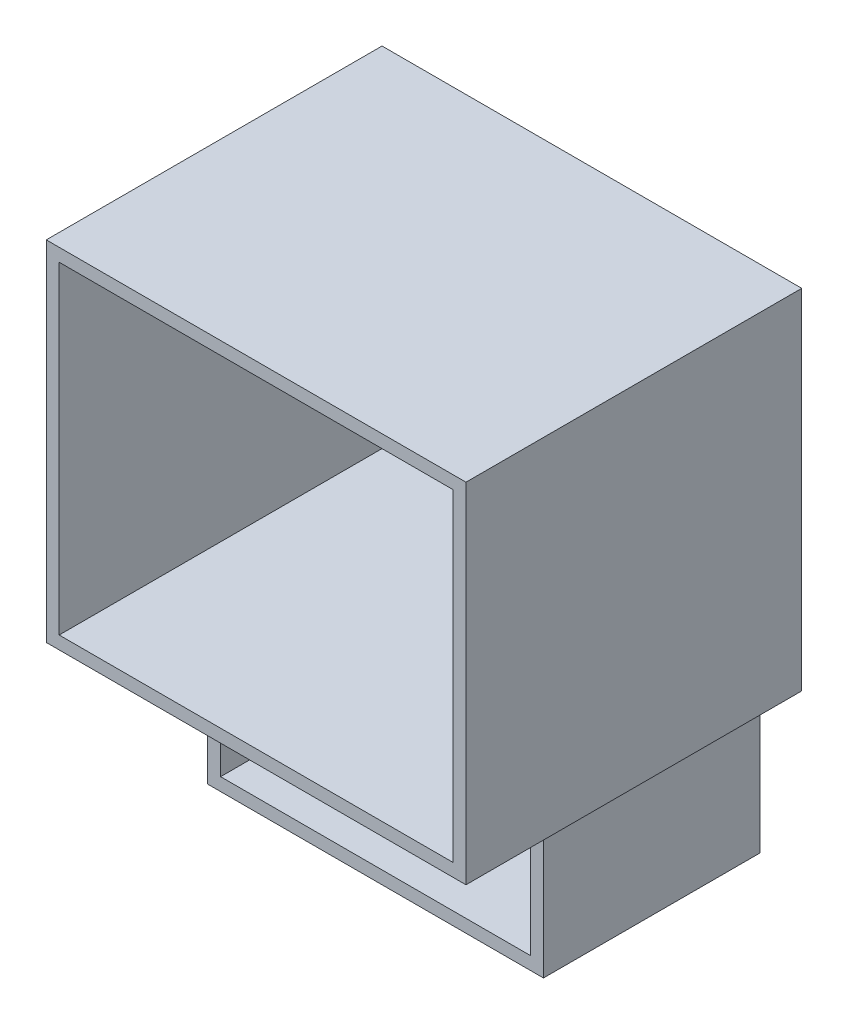
SolidWorks part; units mm, degrees
ref_plane "前视基准面" through (0, 0, 0) normal (0, 0, 1) x (1, 0, 0)
ref_plane "上视基准面" through (0, 0, 0) normal (0, 1, 0) x (1, 0, 0)
ref_plane "右视基准面" through (0, 0, 0) normal (1, 0, 0) x (0, 0, -1)
other "Configuration Table"
sketch "草图1" plane through (0, 0, 0) normal (0, 0, 1) x (1, 0, 0)
  line L0 (0, 39.3558) -> (0, -33.9703) construction
  line L1 (-32.5, -27) -> (32.5, -27)
  line L2 (-32.5, -27) -> (-32.5, 27)
  line L3 (-32.5, 27) -> (32.5, 27)
  line L4 (32.5, -27) -> (32.5, 27)
  line L5 (-32.5, -27) -> (32.5, 27) construction
  line L6 (-32.5, 27) -> (32.5, -27) construction
  line L7 (-53.3932, 0) -> (51.8921, 0) construction
  line L8 (-26, 18.5) -> (-26, -18.5) construction
  circle A0 centre (-26, 18.5) radius 1.5
  circle A1 centre (26, 18.5) radius 1.5
  circle A2 centre (-26, -18.5) radius 1.5
  circle A3 centre (26, -18.5) radius 1.5
  point P0 (0, 0)
  point P26 (0, 0)
  dimension "D2" = 18.5
  dimension "D5" = 3
  dimension "D1" = 26
  dimension "D3" = 65
  dimension "D4" = 54
extrude "凸台-拉伸1" add sketch "草图1" along normal blind 2
sketch "草图2" plane through (0, 0, 2) normal (0, 0, 1) x (1, 0, 0)
  line L1 (-30.5, -25) -> (30.5, -25)
  line L2 (-30.5, -25) -> (-30.5, 25)
  line L3 (-30.5, 25) -> (30.5, 25)
  line L4 (30.5, -25) -> (30.5, 25)
  line L5 (-30.5, -25) -> (30.5, 25) construction
  line L6 (-30.5, 25) -> (30.5, -25) construction
  line L7 (-32.5, -27) -> (32.5, -27)
  line L8 (-32.5, -27) -> (-32.5, 27)
  line L9 (-32.5, 27) -> (32.5, 27)
  line L10 (32.5, -27) -> (32.5, 27)
  line L11 (-32.5, -27) -> (32.5, 27) construction
  line L12 (-32.5, 27) -> (32.5, -27) construction
  point P1 (0, 0)
  point P6 (0, 0)
  dimension "D1" = 2
  dimension "D2" = 2
extrude "凸台-拉伸2" add sketch "草图2" along normal blind 50
sketch "草图6" plane through (0, 0, 0) normal (0, 0, 1) x (1, 0, 0)
  line L0 (0, 34.1484) -> (0, -37.6041) construction
  line L1 (-32.5, -27) -> (32.5, -27) construction
  line L2 (-26, -52) -> (26, -52)
  line L3 (-26, -52) -> (-26, -27)
  line L4 (-26, -27) -> (26, -27)
  line L5 (26, -52) -> (26, -27)
  line L6 (-26, -52) -> (26, -27) construction
  line L7 (-26, -27) -> (26, -52) construction
  circle A0 centre (-18.8, -30) radius 1.8
  circle A1 centre (18.8, -30) radius 1.8
  point P3 (0, -39.5)
  dimension "D3" = 37.6
  dimension "D4" = 3
  dimension "D5" = 3.6
  dimension "D1" = 25
  dimension "D2" = 52
extrude "凸台-拉伸3" add sketch "草图6" along normal blind 3.5
sketch "草图7" plane through (0, 0, 3.5) normal (0, 0, 1) x (1, 0, 0)
  line L6 (-26, -27) -> (26, -27)
  line L7 (-26, -27) -> (-26, -52)
  line L8 (-26, -52) -> (26, -52)
  line L9 (26, -27) -> (26, -52)
  line L10 (-24, -27) -> (24, -27)
  line L11 (-24, -27) -> (-24, -50)
  line L12 (-24, -50) -> (24, -50)
  line L13 (24, -27) -> (24, -50)
  dimension "D1" = 2
  dimension "D2" = 2
  dimension "D3" = 2
extrude "凸台-拉伸4" add sketch "草图7" along normal blind 30 contours L13 L6 L11 L12
sketch "草图8" plane through (0, 0, 0) normal (0, 0, -1) x (-1, 0, 0)
  circle A0 centre (-18.8, -30) radius 3.1
  circle A1 centre (18.8, -30) radius 3.1
  dimension "D1" = 6.2
  dimension "D2" = 6.2
extrude "切除-拉伸1" cut sketch "草图8" against normal blind 2.5
